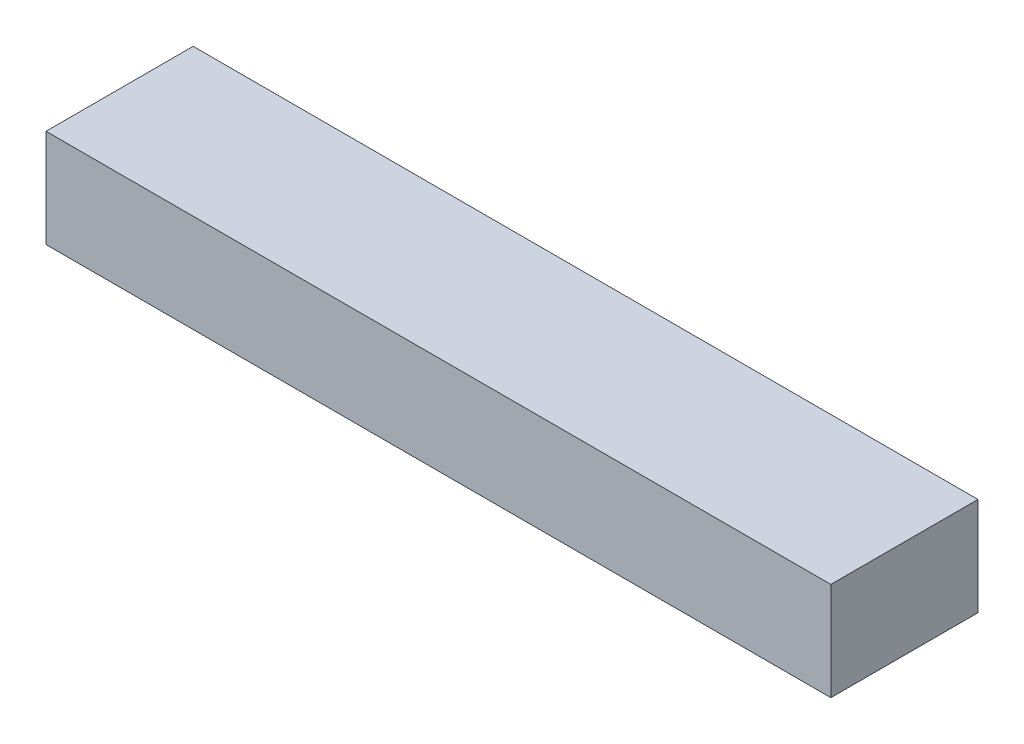
SolidWorks part; units mm, degrees
material "Balsa"
ref_plane "Front Plane" through (0, 0, 0) normal (0, 0, 1) x (1, 0, 0)
ref_plane "Top Plane" through (0, 0, 0) normal (0, 1, 0) x (1, 0, 0)
ref_plane "Right Plane" through (0, 0, 0) normal (1, 0, 0) x (0, 0, -1)
sketch "Sketch1" plane through (0, 0, 0) normal (0, 1, 0) x (1, 0, 0)
  line L1 (-203.2, -38.1) -> (203.2, -38.1)
  line L2 (-203.2, -38.1) -> (-203.2, 38.1)
  line L3 (-203.2, 38.1) -> (203.2, 38.1)
  line L4 (203.2, -38.1) -> (203.2, 38.1)
  line L5 (0, 38.1) -> (0, -38.1) construction
  line L6 (-203.2, 0) -> (203.2, 0) construction
  point P0 (0, 0)
  dimension "D1" = 406.4
  dimension "D2" = 76.2
extrude "Boss-Extrude1" add sketch "Sketch1" along normal blind 50.8
ref_plane "Plane1" through (0, 0, 0) normal (1, 0, 0) x (0, 0, -1)
